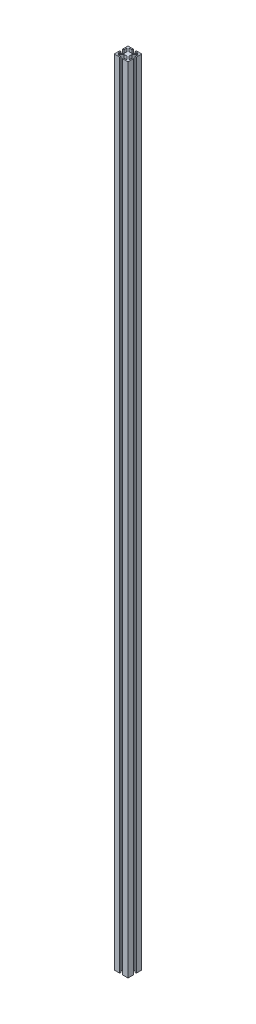
SolidWorks part; units mm, degrees
ref_plane "Front Plane" through (0, 0, 0) normal (0, 0, 1) x (1, 0, 0)
ref_plane "Top Plane" through (0, 0, 0) normal (0, 1, 0) x (1, 0, 0)
ref_plane "Right Plane" through (0, 0, 0) normal (1, 0, 0) x (0, 0, -1)
sketch "Sketch1" plane through (11.365, 0, 9.8462) normal (0, 1, 0) x (1, 0, 0)
  line L0 (-11.365, 9.8462) -> (-11.365, 32.3924) construction
  line L1 (-11.365, 9.8462) -> (-35.43, 9.8462) construction
  line L2 (-11.365, 9.8462) -> (-7.5972, 6.0784) construction
  line L3 (-24.065, 22.5462) -> (-14.2298, 22.5462)
  line L4 (-14.2298, 22.5462) -> (-14.2298, 20.3364)
  line L5 (-14.2298, 20.3364) -> (-20.2926, 20.3364)
  line L6 (-20.2926, 20.3364) -> (-14.3109, 14.3547)
  line L7 (-14.3109, 14.3547) -> (-8.4191, 14.3547)
  line L8 (-15.8735, 12.7921) -> (-15.8735, 6.9003)
  line L9 (-21.8552, 18.7738) -> (-15.8735, 12.7921)
  line L10 (-21.8552, 12.711) -> (-21.8552, 18.7738)
  line L11 (-24.065, 12.711) -> (-21.8552, 12.711)
  line L12 (-24.065, 22.5462) -> (-24.065, 12.711)
  line L13 (-14.3109, 5.3377) -> (-8.4191, 5.3377)
  line L14 (-20.2926, -0.644) -> (-14.3109, 5.3377)
  line L15 (-21.8552, 0.9186) -> (-15.8735, 6.9003)
  line L16 (-21.8552, 6.9814) -> (-21.8552, 0.9186)
  line L17 (-24.065, 6.9814) -> (-21.8552, 6.9814)
  line L18 (-24.065, -2.8538) -> (-24.065, 6.9814)
  line L19 (-14.2298, -0.644) -> (-20.2926, -0.644)
  line L20 (-14.2298, -2.8538) -> (-14.2298, -0.644)
  line L21 (-24.065, -2.8538) -> (-14.2298, -2.8538)
  line L22 (1.335, -2.8538) -> (-8.5002, -2.8538)
  line L23 (-8.5002, -2.8538) -> (-8.5002, -0.644)
  line L24 (-8.5002, -0.644) -> (-2.4374, -0.644)
  line L25 (1.335, -2.8538) -> (1.335, 6.9814)
  line L26 (1.335, 6.9814) -> (-0.8748, 6.9814)
  line L27 (-0.8748, 6.9814) -> (-0.8748, 0.9186)
  line L28 (-0.8748, 0.9186) -> (-6.8565, 6.9003)
  line L29 (-2.4374, -0.644) -> (-8.4191, 5.3377)
  line L30 (1.335, 22.5462) -> (1.335, 12.711)
  line L31 (1.335, 12.711) -> (-0.8748, 12.711)
  line L32 (-0.8748, 12.711) -> (-0.8748, 18.7738)
  line L33 (-0.8748, 18.7738) -> (-6.8565, 12.7921)
  line L34 (-6.8565, 12.7921) -> (-6.8565, 6.9003)
  line L35 (-2.4374, 20.3364) -> (-8.4191, 14.3547)
  line L36 (-8.5002, 20.3364) -> (-2.4374, 20.3364)
  line L37 (-8.5002, 22.5462) -> (-8.5002, 20.3364)
  line L38 (1.335, 22.5462) -> (-8.5002, 22.5462)
  point P20 (-15.8735, 9.8462)
  point P26 (-6.8565, 9.8462)
  point P36 (-11.365, 5.3377)
  point P42 (-11.365, 14.3547)
  dimension "D1" = 9.8352
  dimension "D2" = 12.7
  dimension "D3" = 4.5085
  dimension "D4" = 2.2098
  dimension "D5" = 1.1049
extrude "Boss-Extrude1" add sketch "Sketch1" along normal offset from surface (1470.1838 mm away) 30.48
other "1010<1>"
